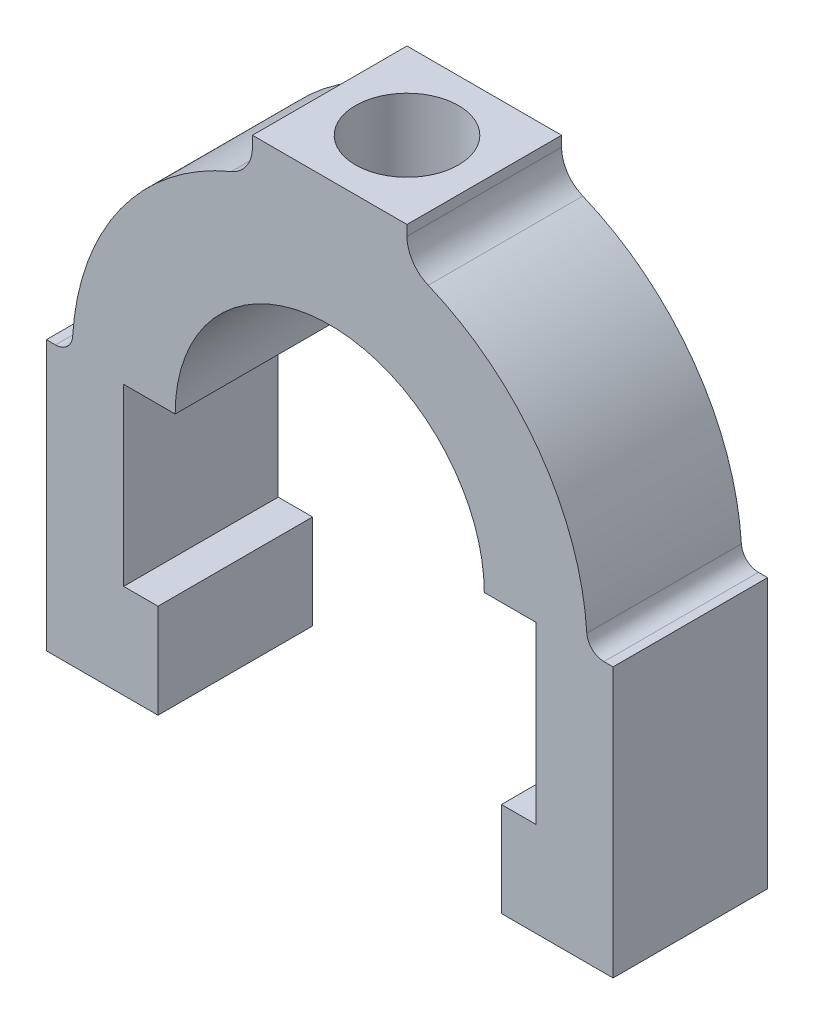
SolidWorks part; units mm, degrees
ref_plane "Front Plane" through (0, 0, 0) normal (0, 0, 1) x (1, 0, 0)
ref_plane "Top Plane" through (0, 0, 0) normal (0, 1, 0) x (1, 0, 0)
ref_plane "Right Plane" through (0, 0, 0) normal (1, 0, 0) x (0, 0, -1)
sketch "Sketch1" plane through (0, 0, 0) normal (0, 0, 1) x (1, 0, 0)
  line L0 (-30, 0) -> (-33, 0)
  line L1 (-33, 0) -> (-33, -31.3818)
  line L2 (-33, -31.3818) -> (-20, -31.3818)
  line L3 (-20, -31.3818) -> (-20, -20.3818)
  line L4 (-20, -20.3818) -> (-24, -20.3818)
  line L5 (-24, -20.3818) -> (-24, 0)
  line L6 (-24, 0) -> (-18, 0)
  line L7 (0, -55) -> (0, 55) construction
  line L8 (24, 0) -> (18, 0)
  line L9 (24, -20.3818) -> (24, 0)
  line L10 (20, -20.3818) -> (24, -20.3818)
  line L11 (20, -31.3818) -> (20, -20.3818)
  line L12 (33, -31.3818) -> (20, -31.3818)
  line L13 (33, 0) -> (33, -31.3818)
  line L14 (30, 0) -> (33, 0)
  line L15 (0, 0) -> (0, -35.277) construction
  line L17 (-9, 32.6182) -> (9, 32.6182)
  line L18 (-9, 32.6182) -> (-9, 28.6182)
  line L20 (9, 32.6182) -> (9, 28.6182)
  arc A0 (-30, 0) -> (-9, 28.6182) centre (0, 0) cw
  arc A1 (-18, 0) -> (18, 0) centre (0, 0) cw
  arc A2 (9, 28.6182) -> (30, 0) centre (0, 0) cw
  arc A3 (-30, 0) -> (30, 0) centre (0, 0) cw construction
  dimension "D2" = 30
  dimension "D3" = 13
  dimension "D4" = 9
  dimension "D5" = 64
  dimension "D6" = 66
  dimension "D7" = 11
  dimension "D8" = 18
  dimension "D9" = 60
  dimension "D1" = 12
extrude "Boss-Extrude1" add sketch "Sketch1" along normal mid plane 18
fillet "Fillet1" radius 4 2 edges at (-9, 28.6182, 0) (9, 28.6182, 0)
fillet "Fillet2" radius 2 2 edges at (-30, 0, 0) (30, 0, 0)
hole_wizard "Hole1" positions "Sketch2" profile "Sketch3" legacy end condition up to next
sketch "Sketch2" plane through (0, 32.6182, 0) normal (0, 1, 0) x (1, 0, 0)
  point P0 (0, 0)
sketch "Sketch3" plane through (0, 32.6182, 0) normal (1, 0, 0) x (0, 0, 1)
  line L0 (0, 0) -> (0, 14.6182)
  line L1 (0, 14.6182) -> (6, 14.6182)
  line L2 (6, 14.6182) -> (6, 0)
  line L3 (6, 0) -> (0, 0)
  line L4 (0, 110) -> (0, -10) construction
  dimension "Diameter" = 12
  dimension "Depth" = 14.6182
